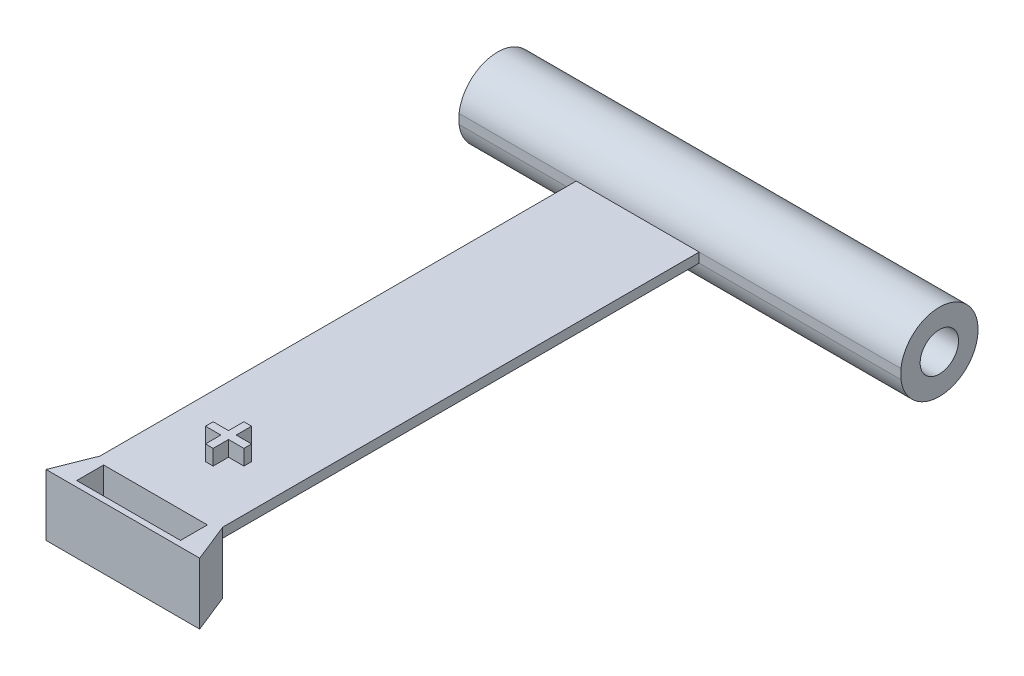
SolidWorks part; units mm, degrees
ref_plane "Front Plane" through (0, 0, 0) normal (0, 0, 1) x (1, 0, 0)
ref_plane "Top Plane" through (0, 0, 0) normal (0, 1, 0) x (1, 0, 0)
ref_plane "Right Plane" through (0, 0, 0) normal (1, 0, 0) x (0, 0, -1)
sketch "Sketch4" plane through (0, 0, 0) normal (0, 1, 0) x (1, 0, 0)
  line L0 (0, 0) -> (0, 20)
  line L1 (0, 0) -> (80, 0)
  line L2 (0, 0) -> (0, 20)
  line L3 (0, 20) -> (80, 20)
  line L4 (80, 0) -> (80, 20)
  line L5 (0, 20) -> (8, 20)
  line L6 (0, 0) -> (8, 20)
  line L7 (80, 20) -> (72, 20)
  line L8 (72, 20) -> (80, 0)
extrude "Boss-Extrude2" add sketch "Sketch4" along normal blind 32 contours L8 L3 L6 L1
sketch "Sketch5" plane through (0, 32, 0) normal (0, 1, 0) x (1, 0, 0)
  line L0 (8, 20) -> (13, 20)
  line L2 (8, 20) -> (72, 20) construction
  line L3 (13, 20) -> (13, 17)
  line L4 (0, 0) -> (80, 0) construction
  line L5 (13, 0) -> (13, 3)
  line L6 (13, 17) -> (13, 3)
  line L7 (72, 20) -> (67, 20)
  line L8 (67, 20) -> (67, 3)
  line L9 (67, 3) -> (13, 3)
  line L10 (13, 17) -> (67, 17)
extrude "Cut-Extrude1" cut sketch "Sketch5" against normal blind 32 contours L10 L6 L9 L8
sketch "Sketch6" plane through (0, 0, -20) normal (0, 0, -1) x (-1, 0, 0)
  line L0 (-72, 32) -> (-72, 27)
  line L1 (-72, 32) -> (-72, 0) construction
  line L2 (-72, 27) -> (-8, 27)
  line L3 (-8, 32) -> (-8, 0) construction
  line L4 (-8, 27) -> (-8, 32)
  line L5 (-8, 32) -> (-72, 32)
extrude "Boss-Extrude3" add sketch "Sketch6" along normal blind 70
sketch "Sketch7" plane through (0, 32, 0) normal (0, 1, 0) x (1, 0, 0)
  line L0 (8, 55) -> (72, 55)
  line L1 (8, 90) -> (8, 20) construction
  line L2 (72, 90) -> (72, 20) construction
  line L3 (72, 55) -> (40, 55)
  line L4 (40, 55) -> (40, 65)
  line L5 (40, 65) -> (40, 55)
  line L6 (40, 55) -> (40, 45)
  line L7 (40, 45) -> (42, 45)
  line L8 (42, 45) -> (42, 65)
  line L9 (42, 65) -> (40, 65)
  line L10 (40, 45) -> (38, 45)
  line L11 (38, 45) -> (38, 65)
  line L12 (38, 65) -> (40, 65)
  line L13 (40, 55) -> (40, 57)
  line L14 (40, 57) -> (50, 57)
  line L15 (50, 57) -> (50, 53)
  line L16 (50, 53) -> (40, 53)
  line L17 (40, 53) -> (30, 53)
  line L18 (30, 53) -> (30, 57)
  line L19 (30, 57) -> (40, 57)
extrude "Boss-Extrude4" add sketch "Sketch7" along normal blind 8 contours L5 L14 L8 L9 | L11 L19 L5 L12 | L19 L11 L0 L4 | L14 L4 L0 L8 | L19 L18 L0 L11 | L18 L17 L11 L0 | L17 L6 L0 L11 | L16 L8 L0 L6 | L8 L16 L6 L7 | L6 L17 L11 L10 | L16 L15 L3 L8 | L15 L14 L8 L3
sketch "Sketch8" plane through (0, 0, -90) normal (0, 0, -1) x (-1, 0, 0)
  line L0 (-8, 32) -> (-72, 32) construction
  line L1 (-72, 27) -> (-8, 27)
  line L2 (-72, 27) -> (-72, 32)
  line L3 (-72, 32) -> (-8, 32)
  line L4 (-8, 27) -> (-8, 32)
  line L5 (-8, 27) -> (-8, 32) construction
extrude "Boss-Extrude5" add sketch "Sketch8" along normal blind 178
sketch "Sketch13" plane through (72, 0, 0) normal (1, 0, 0) x (0, 0, -1)
  line L0 (268, 29.5) -> (288, 29.5)
  line L1 (268, 32) -> (268, 27) construction
  circle A0 centre (288, 29.5) radius 20.1556
extrude "Boss-Extrude7" add sketch "Sketch13" along normal blind 105 and the other way blind 125
sketch "Sketch14" plane through (177, 0, 0) normal (1, 0, 0) x (0, 0, -1)
  line L0 (288, 49.6556) -> (288, 9.3444)
  arc A0 (268, 27) -> (268, 32) centre (288, 29.5) ccw construction
  circle A1 centre (288, 29.5) radius 10
extrude "Cut-Extrude4" cut sketch "Sketch14" against normal blind 264 contours L0 A1 | L0 A1
